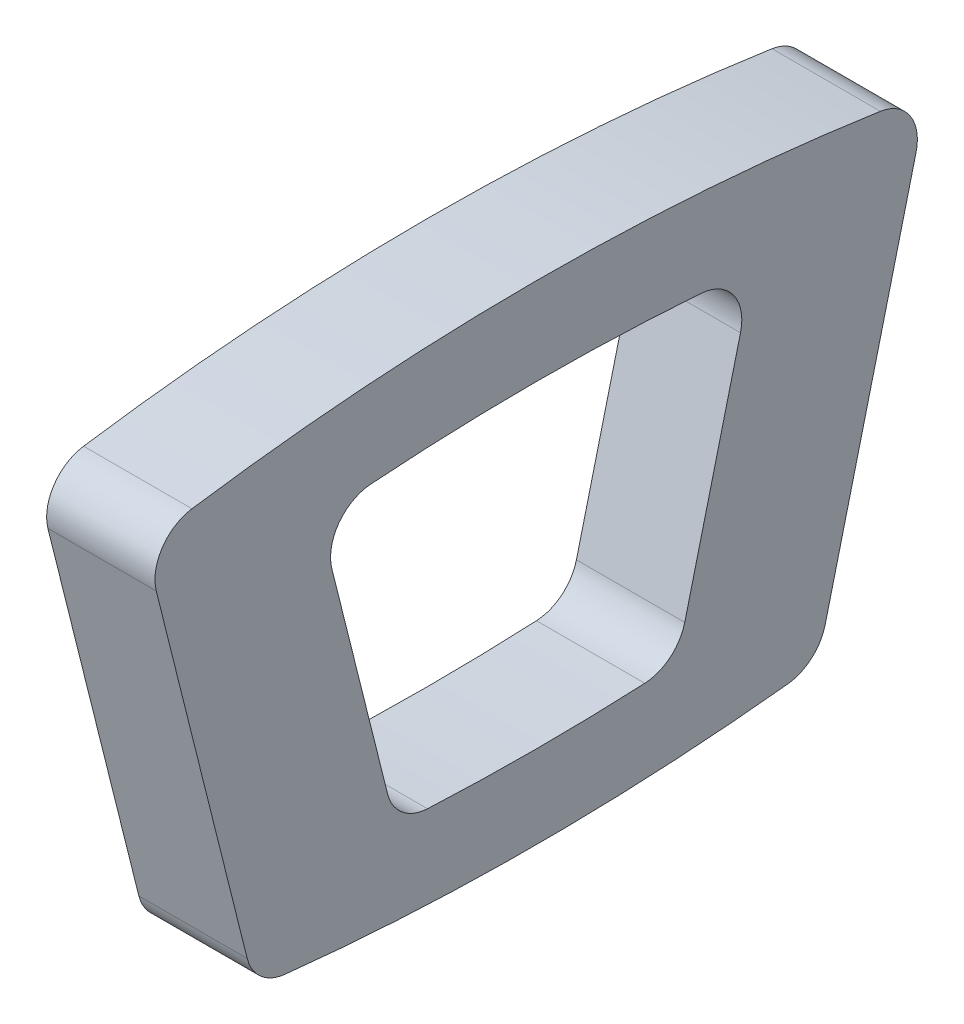
SolidWorks part; units mm, degrees
ref_plane "Спереди" through (0, 0, 0) normal (0, 0, 1) x (1, 0, 0)
ref_plane "Сверху" through (0, 0, 0) normal (0, 1, 0) x (1, 0, 0)
ref_plane "Справа" through (0, 0, 0) normal (1, 0, 0) x (0, 0, -1)
sketch "Эскиз1" plane through (0, 0, 0) normal (1, 0, 0) x (0, 0, -1)
  line L0 (13.7153, 182.8612) -> (18.8603, 203.441)
  line L1 (-13.7153, 182.8612) -> (-18.8603, 203.441)
  line L2 (0, 0) -> (0, 218) construction
  line L3 (26.6724, 176.1896) -> (35.0647, 209.7586)
  line L4 (-26.6724, 176.1896) -> (-35.0647, 209.7586)
  arc A0 (-10.0267, 179.8359) -> (10.0267, 179.8359) centre (0, 388.5545) ccw
  arc A1 (-15.272, 208.4005) -> (15.272, 208.4005) centre (0, 0) cw
  arc A2 (-23.2198, 173.1827) -> (23.2198, 173.1827) centre (0, 388.9606) ccw
  arc A3 (-31.7696, 214.6857) -> (31.7696, 214.6857) centre (0, 0) cw
  arc A4 (10.0267, 179.8359) -> (13.7153, 182.8612) centre (9.8347, 183.8313) ccw
  arc A5 (15.272, 208.4005) -> (18.8603, 203.441) centre (14.9797, 204.4112) cw
  arc A6 (-13.7153, 182.8612) -> (-10.0267, 179.8359) centre (-9.8347, 183.8313) ccw
  arc A7 (-18.8603, 203.441) -> (-15.272, 208.4005) centre (-14.9797, 204.4112) cw
  arc A8 (23.2198, 173.1827) -> (26.6724, 176.1896) centre (22.7918, 177.1597) ccw
  arc A9 (31.7696, 214.6857) -> (35.0647, 209.7586) centre (31.1841, 210.7288) cw
  arc A10 (-26.6724, 176.1896) -> (-23.2198, 173.1827) centre (-22.7918, 177.1597) ccw
  arc A11 (-35.0647, 209.7586) -> (-31.7696, 214.6857) centre (-31.1841, 210.7288) cw
  dimension "D2" = 4
  dimension "D1" = 4
  dimension "D3" = 4
  dimension "D4" = 4
  dimension "D6" = 4
  dimension "D5" = 4
  dimension "D8" = 4
  dimension "D9" = 4
  dimension "D7" = 14.1883
extrude "Вытянуть1" add sketch "Эскиз1" along normal blind 10
